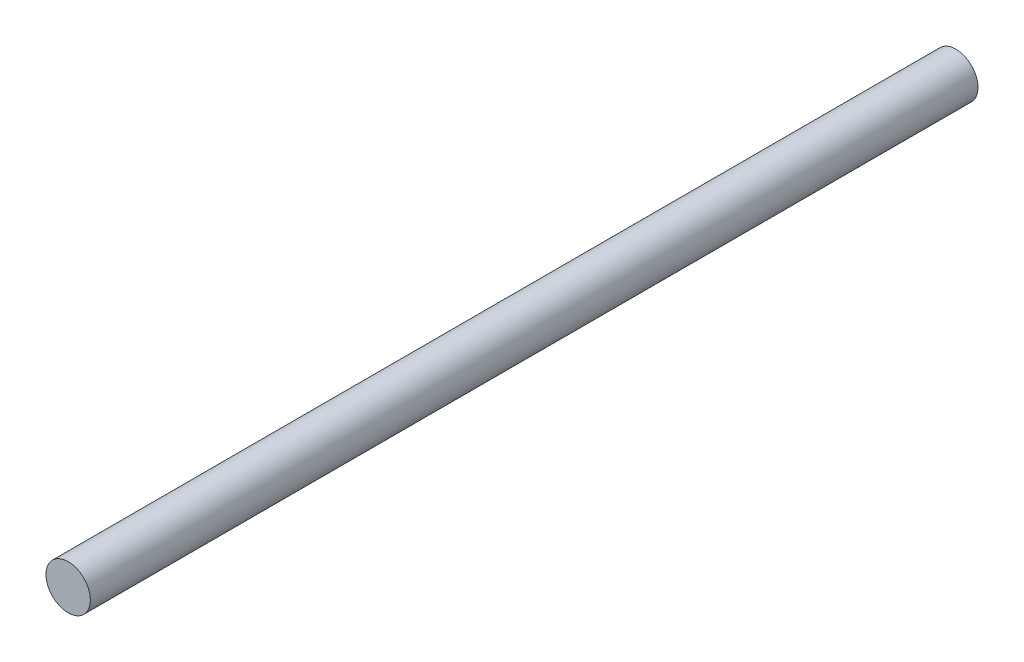
SolidWorks part; units mm, degrees
ref_plane "前视基准面" through (0, 0, 0) normal (0, 0, 1) x (1, 0, 0)
ref_plane "上视基准面" through (0, 0, 0) normal (0, 1, 0) x (1, 0, 0)
ref_plane "右视基准面" through (0, 0, 0) normal (1, 0, 0) x (0, 0, -1)
other "Configuration Table"
sketch "草图1" plane through (0, 0, 0) normal (0, 0, 1) x (1, 0, 0)
  circle A0 centre (0, 0) radius 7.5
  dimension "D1" = 15
extrude "凸台-拉伸1" add sketch "草图1" along normal blind 300
